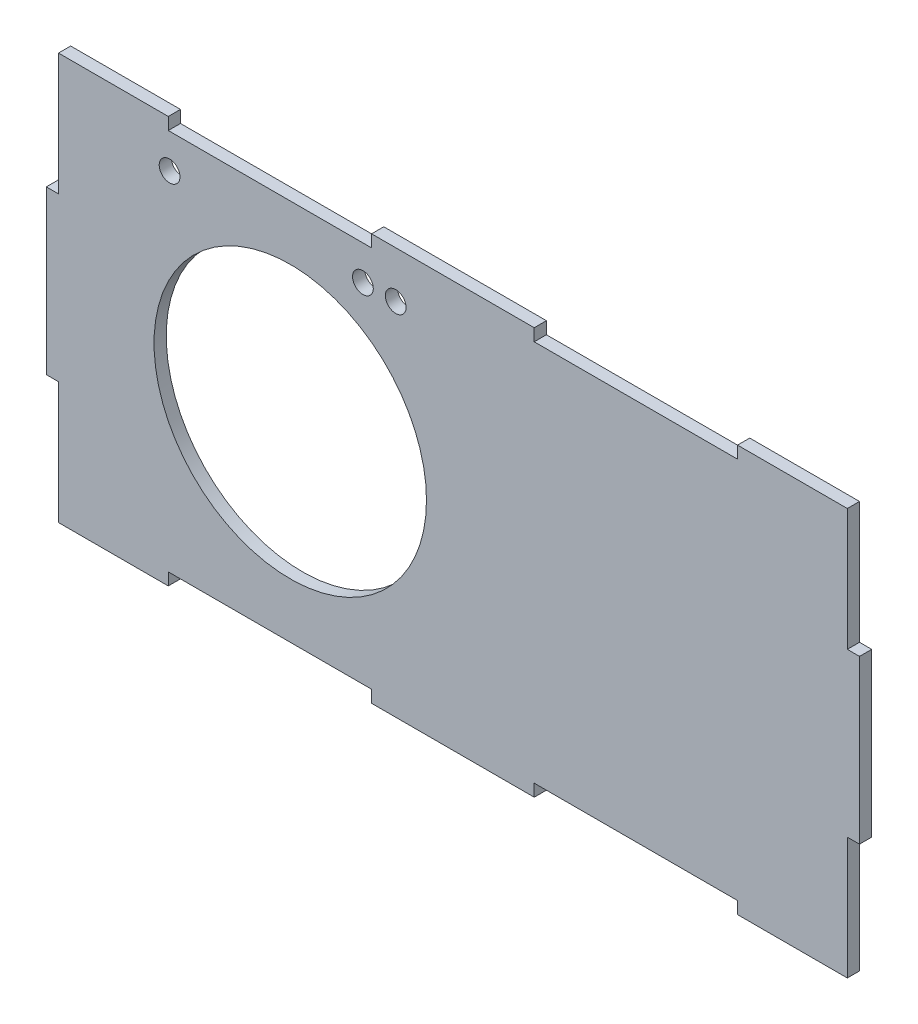
SolidWorks part; units mm, degrees
ref_plane "Plan de face" through (0, 0, 0) normal (0, 0, 1) x (1, 0, 0)
ref_plane "Plan de dessus" through (0, 0, 0) normal (0, 1, 0) x (1, 0, 0)
ref_plane "Plan de droite" through (0, 0, 0) normal (1, 0, 0) x (0, 0, -1)
sketch "Esquisse2" plane through (0, 0, 0) normal (0, 0, 1) x (1, 0, 0)
  line L0 (26.9639, 9.1911) -> (66.9639, 9.1911)
  line L1 (-50.0361, 9.1911) -> (-23.0361, 9.1911)
  line L2 (-53.0361, -20.8089) -> (-53.0361, -60.8089)
  line L3 (-50.0361, -90.8089) -> (-23.0361, -90.8089)
  line L4 (146.9639, -20.8089) -> (146.9639, -60.8089)
  line L5 (116.9639, 9.1911) -> (143.9639, 9.1911)
  line L6 (-23.0361, 9.1911) -> (-23.0361, 6.1911)
  line L7 (-23.0361, 6.1911) -> (26.9639, 6.1911)
  line L8 (26.9639, 9.1911) -> (26.9639, 6.1911)
  line L9 (116.9639, -90.8089) -> (143.9639, -90.8089)
  line L10 (66.9639, 9.1911) -> (66.9639, 6.1911)
  line L11 (66.9639, 6.1911) -> (116.9639, 6.1911)
  line L12 (116.9639, 9.1911) -> (116.9639, 6.1911)
  line L14 (-23.0361, -90.8089) -> (-23.0361, -87.8089)
  line L15 (-23.0361, -87.8089) -> (26.9639, -87.8089)
  line L16 (26.9639, -90.8089) -> (26.9639, -87.8089)
  line L17 (26.9639, -90.8089) -> (66.9639, -90.8089)
  line L18 (66.9639, -90.8089) -> (66.9639, -87.8089)
  line L19 (66.9639, -87.8089) -> (116.9639, -87.8089)
  line L20 (116.9639, -90.8089) -> (116.9639, -87.8089)
  line L22 (-50.0361, 9.1911) -> (-50.0361, -20.8089)
  line L23 (-50.0361, -20.8089) -> (-53.0361, -20.8089)
  line L25 (-53.0361, -60.8089) -> (-50.0361, -60.8089)
  line L28 (-50.0361, -60.8089) -> (-50.0361, -90.8089)
  line L29 (146.9639, -60.8089) -> (143.9639, -60.8089)
  line L32 (143.9639, -60.8089) -> (143.9639, -90.8089)
  line L34 (143.9639, 9.1911) -> (143.9639, -20.8089)
  line L35 (143.9639, -20.8089) -> (146.9639, -20.8089)
  circle A0 centre (6.9639, -40.8089) radius 33.5
  dimension "D3" = 67
  dimension "D2" = 200
  dimension "D4" = 3
  dimension "D5" = 50
  dimension "D6" = 40
  dimension "D7" = 30
  dimension "D8" = 30
  dimension "D9" = 47
  dimension "D10" = 60
  dimension "D11" = 100
extrude "Boss.-Extru.1" add sketch "Esquisse2" along normal blind 3
sketch "Esquisse3" plane through (0, 0, 3) normal (0, 0, 1) x (1, 0, 0)
  circle A0 centre (24.835, -2.2598) radius 2.55
  circle A1 centre (32.9038, -2.2598) radius 2.55
  circle A2 centre (-22.7132, -2.2598) radius 2.55
  dimension "D1" = 5.1
extrude "Enlèv. mat.-Extru.1" cut sketch "Esquisse3" against normal up to next
